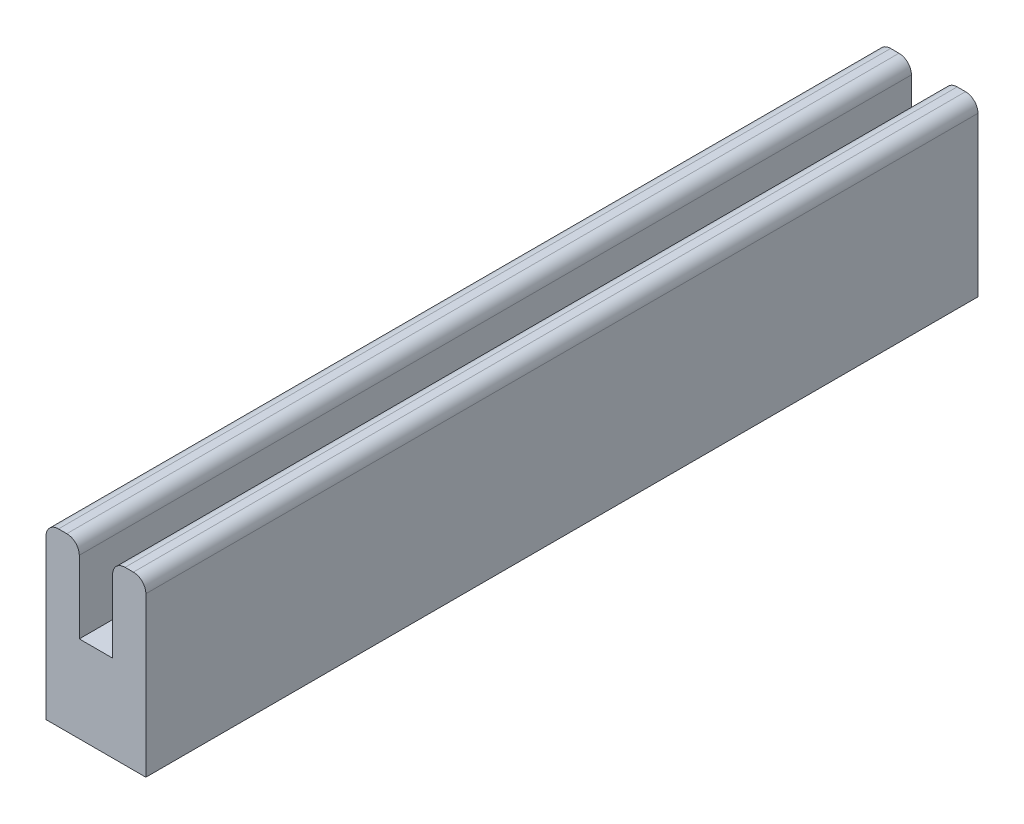
SolidWorks part; units mm, degrees
ref_plane "Plan de face" through (0, 0, 0) normal (0, 0, 1) x (1, 0, 0)
ref_plane "Plan de dessus" through (0, 0, 0) normal (0, 1, 0) x (1, 0, 0)
ref_plane "Plan de droite" through (0, 0, 0) normal (1, 0, 0) x (0, 0, -1)
sketch "Esquisse1" plane through (0, 0, 0) normal (0, 0, 1) x (1, 0, 0)
  line L0 (-4.1207, 5.1) -> (-2.1207, 5.1)
  line L1 (-2.1207, 5.1) -> (-2.1207, 0)
  line L2 (-2.1207, 0) -> (-0.1207, 0)
  line L3 (-0.1207, 0) -> (-0.1207, 5.1)
  line L4 (-0.1207, 5.1) -> (1.8793, 5.1)
  line L5 (1.8793, 5.1) -> (1.8793, -5.2)
  line L6 (1.8793, -5.2) -> (-4.1207, -5.2)
  line L7 (-4.1207, -5.2) -> (-4.1207, 5.1)
  line L8 (-2.1207, 5.1) -> (-0.1207, 5.1) construction
  dimension "D1" = 2
  dimension "D2" = 2
  dimension "D3" = 2
  dimension "D4" = 5.1
  dimension "D5" = 5.2
extrude "Boss.-Extru.1" add sketch "Esquisse1" along normal blind 50
fillet "Congé1" radius 0.75 4 edges at (1.8793, 5.1, 25) (-4.1207, 5.1, 25) (-0.1207, 5.1, 25) (-2.1207, 5.1, 25)
sketch "Esquisse2" plane through (0, -5.2, 0) normal (0, -1, 0) x (1, 0, 0)
  line L1 (-10.1207, 41.7447) -> (-4.1207, 41.7447)
  line L2 (-10.1207, 41.7447) -> (-10.1207, 36.4326)
  line L3 (-10.1207, 36.4326) -> (-4.1207, 36.4326)
  line L4 (-4.1207, 41.7447) -> (-4.1207, 36.4326)
  line L5 (-4.1207, 50) -> (-4.1207, 0) construction
  line L6 (-10.1001, 17.1011) -> (-4.1001, 17.1011)
  line L7 (-10.1001, 17.1011) -> (-10.1001, 11.789)
  line L8 (-10.1001, 11.789) -> (-4.1001, 11.789)
  line L9 (-4.1001, 17.1011) -> (-4.1001, 11.789)
  point P8 (-7.0589, 24.7921)
  point P15 (0, 0)
  dimension "D1" = 6
  dimension "D3" = 6
extrude "Boss.-Extru.2" add sketch "Esquisse2" against normal blind 2
fillet "Congé2" radius 0.5 6 edges at (-7.1207, -3.2, 36.4326) (-7.1207, -3.2, 41.7447) (-10.1207, -3.2, 39.0887) (-7.1104, -3.2, 11.789) (-7.1104, -3.2, 17.1011) (-10.1001, -3.2, 14.4451)
